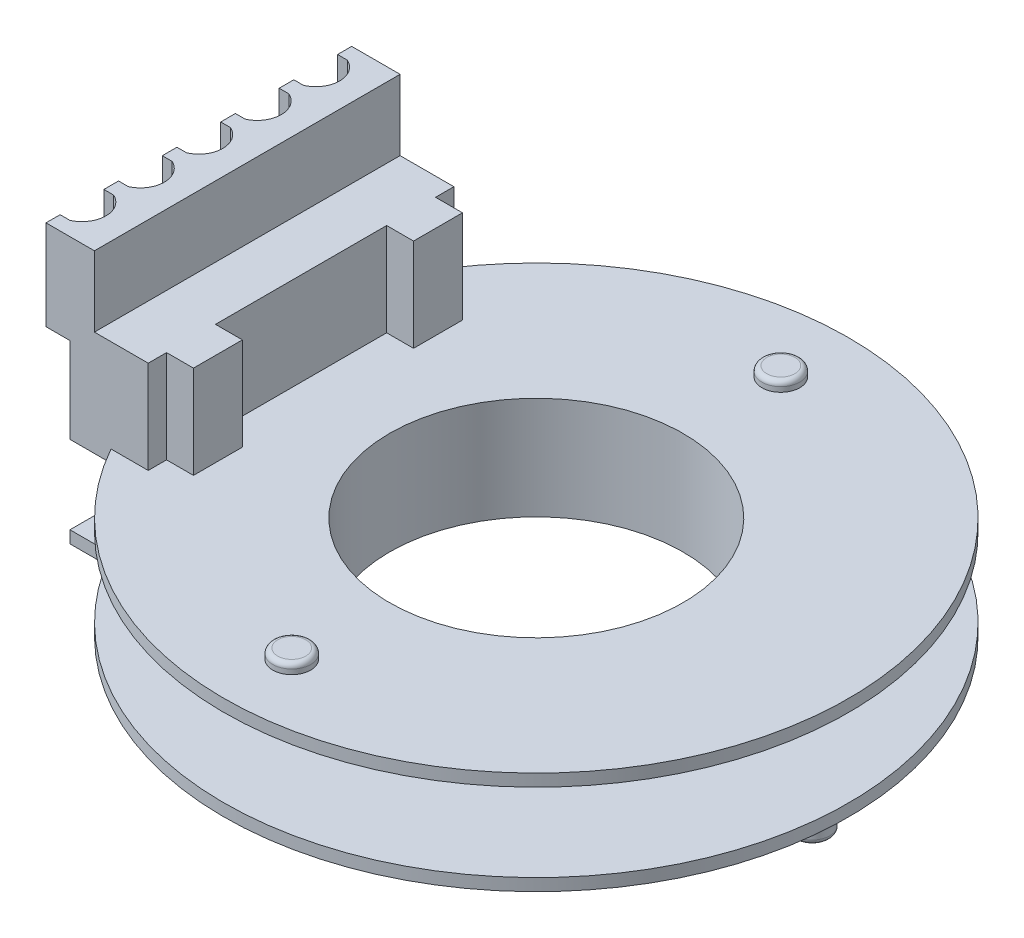
SolidWorks part; units mm, degrees
material "Полиамид ПА-6Б ТУ 6-05-988-93"
ref_plane "Спереди" through (0, 0, 0) normal (0, 0, 1) x (1, 0, 0)
ref_plane "Сверху" through (0, 0, 0) normal (0, 1, 0) x (1, 0, 0)
ref_plane "Справа" through (0, 0, 0) normal (1, 0, 0) x (0, 0, -1)
sketch "Эскиз1" plane through (0, 0, 0) normal (0, 0, 1) x (1, 0, 0)
  line L0 (7, 1.6) -> (7, -1.6)
  line L1 (7, -1.6) -> (12.775, -1.6)
  line L2 (12.775, -1.6) -> (12.775, -2.1)
  line L3 (12.775, -2.1) -> (6, -2.1)
  line L4 (6, -2.1) -> (6, 2.1)
  line L5 (6, 2.1) -> (12.775, 2.1)
  line L6 (12.775, 2.1) -> (12.775, 1.6)
  line L7 (12.775, 1.6) -> (7, 1.6)
  line L8 (6, 0) -> (0, 0) construction
  line L9 (0, 2.1) -> (0, -2.1) construction
  dimension "D1" = 6
  dimension "D2" = 0.5
  dimension "D3" = 1
  dimension "D4" = 4.2
  dimension "D5" = 12.775
revolve "Повернуть1" add sketch "Эскиз1" angle 360 about L9
sketch "Эскиз2" plane through (0, 2.1, 0) normal (0, 1, 0) x (1, 0, 0)
  line L0 (-12.82, 6.25) -> (-9.47, 6.25)
  line L1 (-9.47, 6.25) -> (-9.47, -6.25)
  line L2 (-9.47, -6.25) -> (-12.82, -6.25)
  line L5 (-12.82, -6.25) -> (-12.82, 6.25)
  line L8 (-9.47, 0) -> (0, 0) construction
  point P5 (0, 0)
  point P7 (0, 0)
  point P8 (0, 0)
  dimension "D2" = 12.5
  dimension "D4" = 3.35
  dimension "D5" = 9.47
extrude "Бобышка-Вытянуть1" add sketch "Эскиз2" along normal blind 3.8 and the other way blind 0.5
sketch "Эскиз4" plane through (0, 5.9, 0) normal (0, 1, 0) x (1, 0, 0)
  line L0 (-12.82, 6.25) -> (-12.82, -6.25) construction
  line L1 (-9.47, 6.25) -> (-8.52, 6.25)
  line L2 (-9.47, 6.25) -> (-9.47, -6.25)
  line L3 (-9.47, -6.25) -> (-8.52, -6.25)
  line L4 (-8.52, 6.25) -> (-8.52, -6.25)
  point P5 (0, 0)
  dimension "D1" = 4.3
extrude "Бобышка-Вытянуть2" add sketch "Эскиз4" against normal up to surface (3.8 mm away) up to face at (-6, 2.1, 0)
sketch "Эскиз6" plane through (0, 5.9, 0) normal (0, 1, 0) x (1, 0, 0)
  line L0 (-8.52, -6.25) -> (-8.52, 6.25) construction
  line L1 (-8.52, 6.25) -> (-9.62, 6.25)
  line L2 (-8.52, 6.25) -> (-8.52, 5.5)
  line L3 (-8.52, 5.5) -> (-9.62, 5.5)
  line L4 (-9.62, 6.25) -> (-9.62, 5.5)
  line L5 (-8.52, 3.5) -> (-9.62, 3.5)
  line L6 (-8.52, 3.5) -> (-8.52, -3.5)
  line L7 (-8.52, -3.5) -> (-9.62, -3.5)
  line L8 (-9.62, 3.5) -> (-9.62, -3.5)
  line L9 (-8.52, 0) -> (0, 0) construction
  line L10 (-8.52, -6.25) -> (-9.62, -6.25)
  line L11 (-8.52, -6.25) -> (-8.52, -5.5)
  line L12 (-8.52, -5.5) -> (-9.62, -5.5)
  line L13 (-9.62, -6.25) -> (-9.62, -5.5)
  point P19 (-8.52, 5.875)
  dimension "D1" = 2
  dimension "D2" = 0.75
  dimension "D3" = 1.1
extrude "Вырез-Вытянуть1" cut sketch "Эскиз6" against normal up to surface (3.8 mm away) up to face at (-6, 2.1, 0)
sketch "Эскиз7" plane through (0, 5.9, 0) normal (0, 1, 0) x (1, 0, 0)
  line L0 (-9.62, 6.25) -> (-12.82, 6.25) construction
  line L1 (-11.82, 6.25) -> (-13.8, 6.25)
  line L2 (-11.82, 6.25) -> (-11.82, -6.25)
  line L3 (-11.82, -6.25) -> (-13.8, -6.25)
  line L4 (-13.8, 6.25) -> (-13.8, -6.25)
  line L5 (-12.82, -6.25) -> (-9.62, -6.25) construction
  line L6 (-8.52, 3.5) -> (-8.52, 5.5) construction
  point P6 (0, 0)
  dimension "D1" = 3.3
  dimension "D2" = 1.98
extrude "Бобышка-Вытянуть3" add sketch "Эскиз7" along normal blind 2.88 and the other way blind 0.8
sketch "Эскиз8" plane through (-12.82, 0, 0) normal (-1, 0, 0) x (0, 0, 1)
  line L0 (-6.25, 1.6) -> (6.25, 1.6) construction
  circle A0 centre (-2.4, 2.45) radius 0.425
  circle A1 centre (0, 2.45) radius 0.425
  circle A2 centre (2.4, 2.45) radius 0.425
  point P6 (0, 0)
  point P7 (0, 0)
  dimension "D1" = 0.85
  dimension "D2" = 2.4
  dimension "D3" = 2.4
  dimension "D4" = 0.85
extrude "Бобышка-Вытянуть4" add sketch "Эскиз8" along normal blind 2.4 separate body
sketch "Эскиз9" plane through (0, 8.78, 0) normal (0, 1, 0) x (1, 0, 0)
  line L1 (-13.8, 6.25) -> (-13.8, -6.25) construction
  line L2 (-12.82, 6.25) -> (-12.82, -6.25) construction
  line L3 (-13.4, 3.284) -> (-13.8, 3.284)
  line L4 (-13.4, -1.4947) -> (-13.8, -1.4947)
  line L5 (-13.8, -1.4947) -> (-13.8, -3.284)
  line L6 (-13.4, 0.8947) -> (-13.8, 0.8947)
  line L7 (-13.8, 0.8947) -> (-13.8, -0.8947)
  line L8 (-13.4, 5.6733) -> (-13.8, 5.6733)
  line L9 (-13.8, 5.6733) -> (-13.8, 3.884)
  line L10 (-13.8, 3.884) -> (-13.4, 3.884)
  line L11 (-13.8, 3.284) -> (-13.8, 1.4947)
  line L12 (-13.8, 1.4947) -> (-13.4, 1.4947)
  line L13 (-13.8, -0.8947) -> (-13.4, -0.8947)
  line L14 (-13.8, -3.284) -> (-13.4, -3.284)
  line L15 (-13.4, -3.884) -> (-13.8, -3.884)
  line L16 (-13.8, -3.884) -> (-13.8, -5.6733)
  line L17 (-13.8, -5.6733) -> (-13.4, -5.6733)
  arc A0 (-13.4, 3.884) -> (-13.4, 5.6733) centre (-13.8, 4.7786) ccw
  arc A1 (-13.4, 1.4947) -> (-13.4, 3.284) centre (-13.8, 2.3893) ccw
  arc A2 (-13.4, -0.8947) -> (-13.4, 0.8947) centre (-13.8, 0) ccw
  arc A3 (-13.4, -3.284) -> (-13.4, -1.4947) centre (-13.8, -2.3893) ccw
  arc A4 (-13.4, -5.6733) -> (-13.4, -3.884) centre (-13.8, -4.7786) ccw
  point P19 (0, 0)
  point P20 (0, 0)
  dimension "D1" = 0.6
  dimension "D2" = 0.6
  dimension "D3" = 0.6
  dimension "D4" = 0.6
  dimension "D5" = 0.4
extrude "Вырез-Вытянуть2" cut sketch "Эскиз9" against normal up to surface (3.68 mm away) up to face at (-13.31, 5.1, 0)
sketch "Эскиз10" plane through (0, 2.1, 0) normal (0, 1, 0) x (1, 0, 0)
  circle A0 centre (0, 0) radius 10 construction
  circle A1 centre (0, 10) radius 0.775
  circle A2 centre (0, -10) radius 0.775
  dimension "D1" = 20
  dimension "D2" = 1.55
extrude "Бобышка-Вытянуть5" add sketch "Эскиз10" along normal blind 0.4
sketch "Эскиз11" plane through (0, -2.1, 0) normal (0, -1, 0) x (1, 0, 0)
  line L0 (-11.22, 5.35) -> (-11.22, -5.35) construction
  line L1 (-11.22, 0) -> (0, 0) construction
  circle A0 centre (0, -10) radius 0.775 construction
  circle A1 centre (0, 10) radius 0.775 construction
  circle A2 centre (0, -10) radius 0.775
  circle A3 centre (0, 10) radius 0.775
  circle A4 centre (11.28, 0) radius 0.725
  circle A5 centre (-11.22, 5.35) radius 0.725
  circle A6 centre (-11.22, -5.35) radius 0.725
  dimension "D3" = 1.45
  dimension "D1" = 11.22
  dimension "D2" = 10.7
  dimension "D4" = 11.28
extrude "Бобышка-Вытянуть6" add sketch "Эскиз11" along normal blind 0.4
sketch "Эскиз12" plane through (0, -2.5, 0) normal (0, -1, 0) x (1, 0, 0)
  circle A0 centre (11.28, 0) radius 0.725 construction
  circle A1 centre (-11.22, -5.35) radius 0.725 construction
  circle A2 centre (-11.22, 5.35) radius 0.725 construction
  circle A3 centre (11.28, 0) radius 0.725
  circle A4 centre (-11.22, -5.35) radius 0.725
  circle A5 centre (-11.22, 5.35) radius 0.725
extrude "Бобышка-Вытянуть7" add sketch "Эскиз12" along normal blind 0.85
fillet "Скругление1" radius 0.2 7 edges at (-0.775, 2.5, 10) (-0.775, 2.5, -10) (12.005, -3.35, 0) (-10.495, -3.35, 5.35) (-10.495, -3.35, -5.35) (0.775, -2.5, -10) (0.775, -2.5, 10)
sketch "Эскиз13" plane through (0, -2.1, 0) normal (0, -1, 0) x (1, 0, 0)
  line L0 (-12.82, 6.25) -> (-12.82, -6.25)
  line L1 (-12.82, -6.25) -> (-10.495, -6.25)
  line L2 (-10.495, -6.25) -> (-10.495, 6.25)
  line L3 (-10.495, 6.25) -> (-12.82, 6.25)
  arc A0 (-11.7946, 4.9079) -> (-11.2382, 6.0748) centre (-11.22, 5.35) ccw construction
extrude "Бобышка-Вытянуть8" add sketch "Эскиз13" against normal up to surface (0.5 mm away) up to face at (-7, -1.6, 0)
